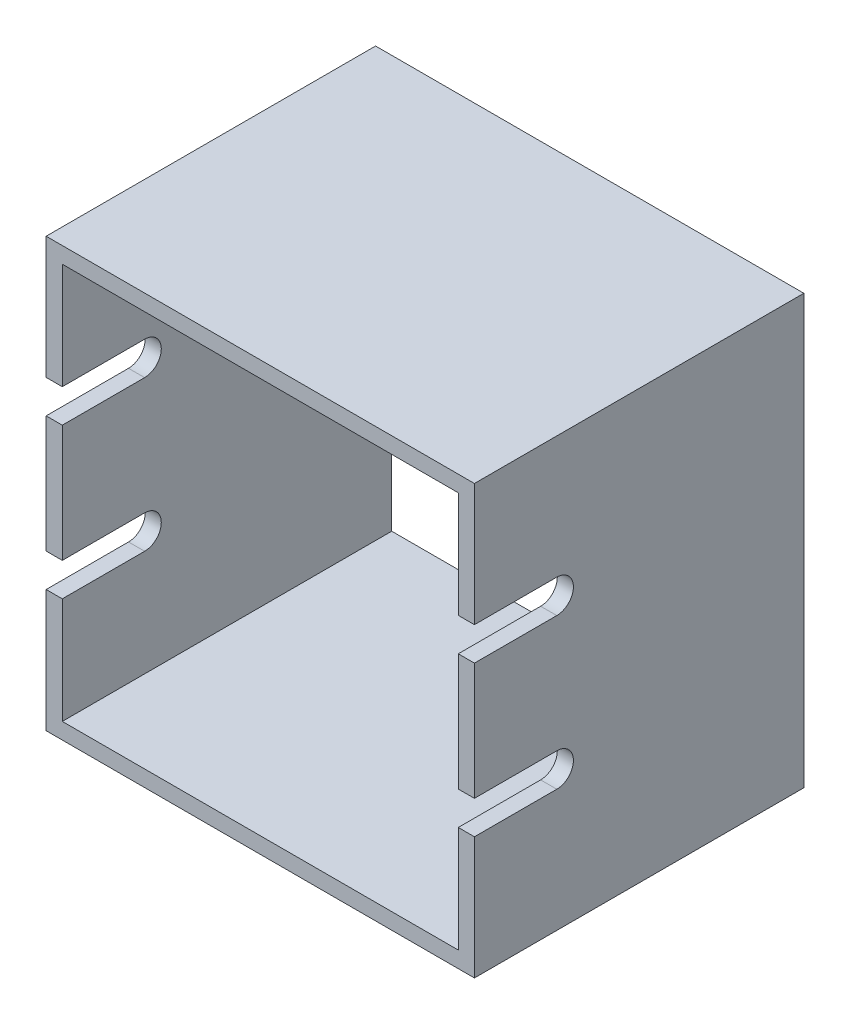
SolidWorks part; units mm, degrees
ref_plane "Front Plane" through (0, 0, 0) normal (1, 0, 0) x (0, 1, 0)
ref_plane "Top Plane" through (0, 0, 0) normal (0, 0, 1) x (0, 1, 0)
ref_plane "Right Plane" through (0, 0, 0) normal (0, 1, 0) x (-1, 0, 0)
sketch "Sketch1" plane through (0, 0, 0) normal (0, 0, 1) x (0, 1, 0)
  line L1 (-65, -65) -> (65, -65)
  line L2 (-65, -65) -> (-65, 65)
  line L3 (-65, 65) -> (65, 65)
  line L4 (65, -65) -> (65, 65)
  line L5 (-65, -65) -> (65, 65) construction
  line L6 (-65, 65) -> (65, -65) construction
  point P0 (0, 0)
  dimension "D1" = 130
extrude "Boss-Extrude1" add sketch "Sketch1" along normal blind 100
sketch "Sketch2" plane through (0, 0, 100) normal (0, 0, 1) x (1, 0, 0)
  line L1 (-60.1, -60.1) -> (60.1, -60.1)
  line L2 (-60.1, -60.1) -> (-60.1, 60.1)
  line L3 (-60.1, 60.1) -> (60.1, 60.1)
  line L4 (60.1, -60.1) -> (60.1, 60.1)
  line L5 (-60.1, -60.1) -> (60.1, 60.1) construction
  line L6 (-60.1, 60.1) -> (60.1, -60.1) construction
  point P0 (0, 0)
  dimension "D1" = 120.2
extrude "Cut-Extrude1" cut sketch "Sketch2" against normal blind 1000
sketch "Sketch3" plane through (-65, 0, 0) normal (-1, 0, 0) x (0, -1, 0)
  line L0 (-65, 100) -> (65, 100) construction
  line L1 (-27.875, 100) -> (-17.775, 100)
  line L2 (-27.875, 100) -> (-27.875, 75)
  line L3 (-27.875, 75) -> (-17.775, 75)
  line L4 (-17.775, 100) -> (-17.775, 75)
  line L5 (0, 0) -> (0, 50000) construction
  line L6 (17.775, 100) -> (17.775, 75)
  line L7 (27.875, 75) -> (17.775, 75)
  line L8 (27.875, 100) -> (27.875, 75)
  line L9 (27.875, 100) -> (17.775, 100)
  circle A0 centre (-22.825, 75) radius 5.05
  circle A1 centre (22.825, 75) radius 5.05
  line M8 (65, 100) -> (-65, 100)
  dimension "D1" = 25
  dimension "D2" = 10.1
  dimension "D3" = 27.875
extrude "Cut-Extrude2" cut sketch "Sketch3" against normal blind 1000 contours L6 A1 L8 M8 | A0 L4 L2 M8 | L3 A0 | L3 A0 | A1 L7 | A1 L7
